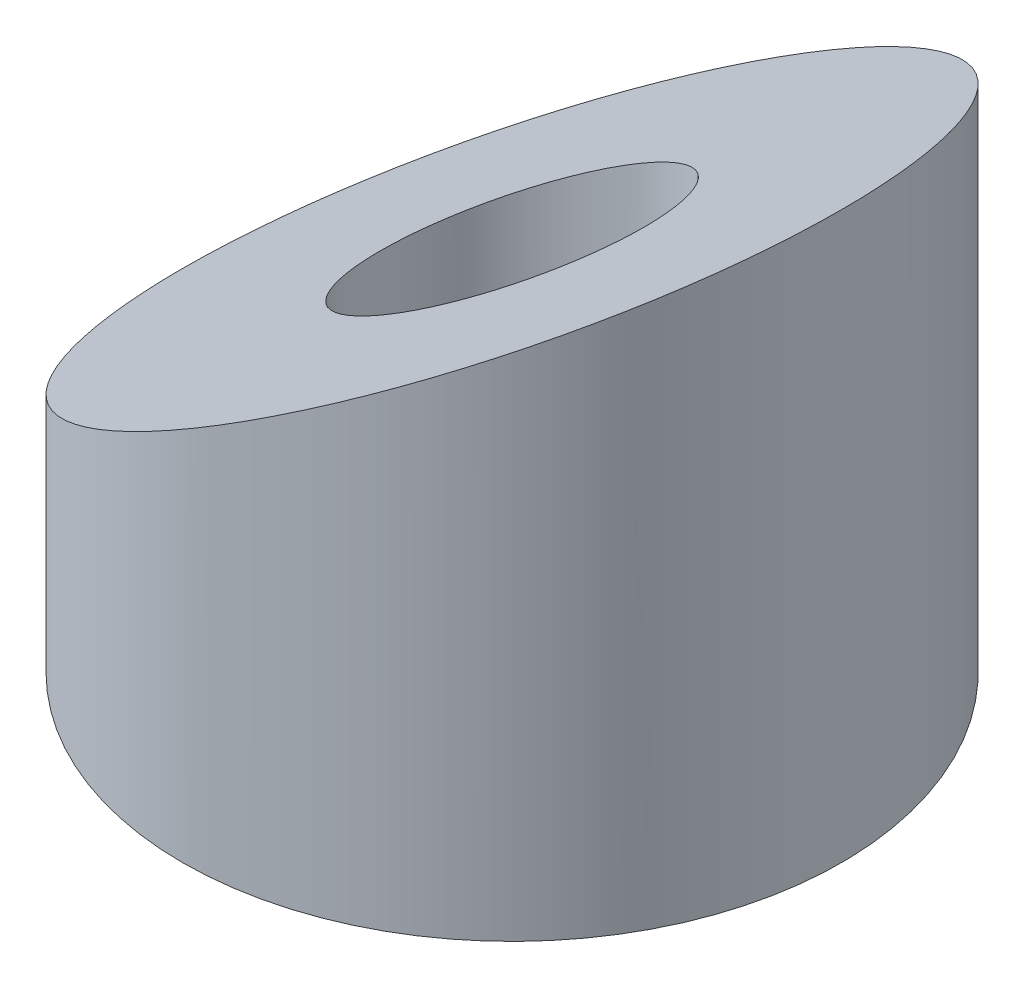
SolidWorks part; units mm, degrees
material "ABS PC"
ref_plane "前视基准面" through (0, 0, 0) normal (0, 0, 1) x (1, 0, 0)
ref_plane "上视基准面" through (0, 0, 0) normal (0, 1, 0) x (1, 0, 0)
ref_plane "右视基准面" through (0, 0, 0) normal (1, 0, 0) x (0, 0, -1)
sketch "草图1" plane through (0, 0, 0) normal (0, 1, 0) x (1, 0, 0)
  circle A0 centre (0, 0) radius 2.5
  circle A1 centre (0, 0) radius 1
  dimension "D1" = 5
  dimension "D2" = 2
extrude "凸台-拉伸1" add sketch "草图1" along normal blind 4.29
sketch "草图2" plane through (0, 0, 0) normal (0, 0, 1) x (1, 0, 0)
  line L0 (2.5, 4.29) -> (-2.5, 1.4032)
  line L1 (-2.5, 4.29) -> (-2.5, 0) construction
  line L2 (-2.5, 1.4032) -> (-2.5, 4.29)
  line L3 (-2.5, 4.29) -> (2.5, 4.29)
  dimension "D1" = 30
extrude "切除-拉伸1" cut sketch "草图2" against normal through all both and the other way through all
